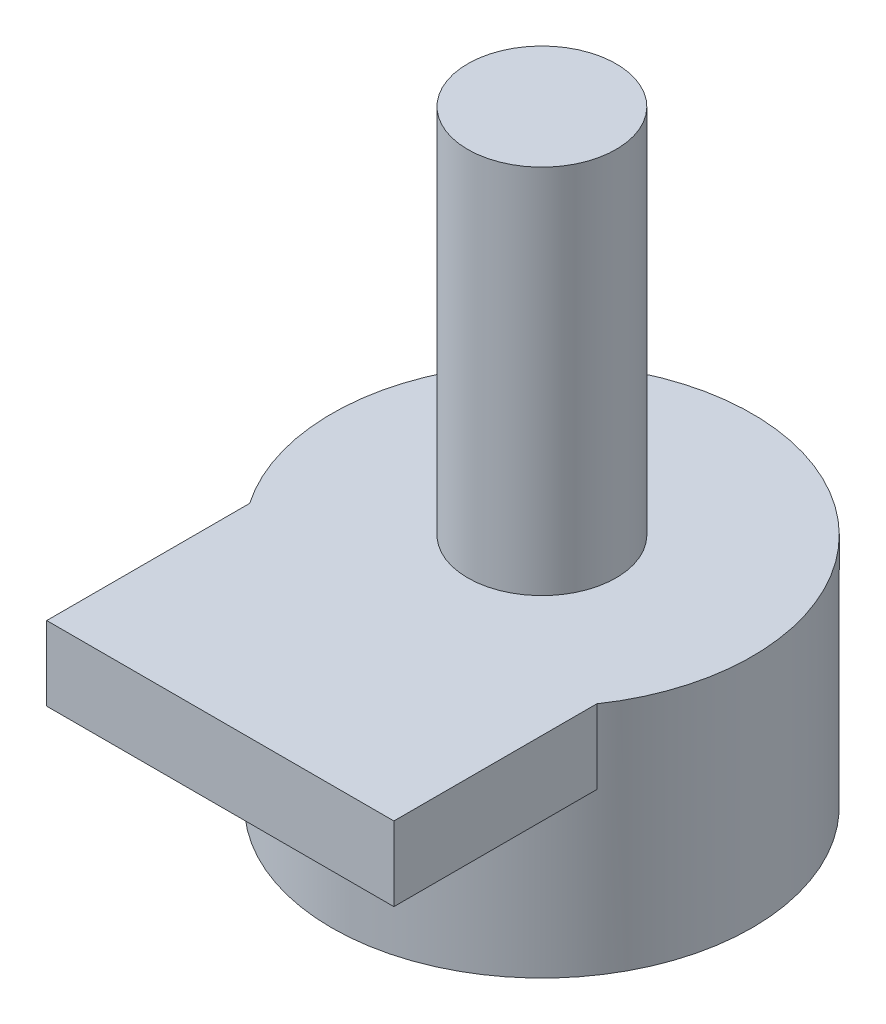
SolidWorks part; units mm, degrees
ref_plane "Front Plane" through (0, 0, 0) normal (0, 0, 1) x (1, 0, 0)
ref_plane "Top Plane" through (0, 0, 0) normal (0, 1, 0) x (1, 0, 0)
ref_plane "Right Plane" through (0, 0, 0) normal (1, 0, 0) x (0, 0, -1)
sketch "Sketch1" plane through (0, 0, 0) normal (0, 1, 0) x (1, 0, 0)
  circle A0 centre (0, 0) radius 8.5
  dimension "D1" = 17
extrude "Boss-Extrude1" add sketch "Sketch1" along normal blind 9.5
sketch "Sketch2" plane through (0, 9.5, 0) normal (0, 1, 0) x (1, 0, 0)
  circle A0 centre (0, 0) radius 3
  dimension "D1" = 6
extrude "Boss-Extrude2" add sketch "Sketch2" along normal blind 15
sketch "Sketch3" plane through (0, 9.5, 0) normal (0, 1, 0) x (1, 0, 0)
  line L0 (-8.4125, 0) -> (8.5, 0)
  line L1 (-8.4125, 0) -> (-8.4125, -13)
  line L2 (8.5, 0) -> (8.5, -13)
  line L3 (-8.4125, -13) -> (8.5, -13)
  line L4 (-9.35, 0) -> (9.35, 0) construction
  circle A0 centre (0, 0) radius 8.5 construction
  dimension "D1" = 13
extrude "Boss-Extrude3" add sketch "Sketch3" against normal blind 3
sketch "Sketch4" plane through (0, 6.5, 0) normal (0, -1, 0) x (1, 0, 0)
  line L0 (-7.0165, 13) -> (-7.0165, 4.7978)
  line L1 (7.0165, 13) -> (7.0165, 4.7978)
  line L2 (-7.0165, 13) -> (-8.4125, 13)
  line L3 (-8.4125, 13) -> (-8.4125, 1.2163)
  line L4 (8.5, 0) -> (8.5, 13)
  line L5 (8.5, 13) -> (-8.4125, 13)
  line L6 (-8.4125, 13) -> (-8.4125, 1.2163)
  line L7 (8.5, 0) -> (8.5, 13)
  line L8 (8.5, 13) -> (7.0165, 13)
  arc A0 (-7.0165, 4.7978) -> (-8.4125, 1.2163) centre (0, 0) ccw
  arc A1 (8.5, 0) -> (-8.4125, 1.2163) centre (0, 0) ccw
  arc A2 (8.5, 0) -> (7.0165, 4.7978) centre (0, 0) ccw
  dimension "D1" = 0
extrude "Cut-Extrude2" cut sketch "Sketch4" against normal through all
